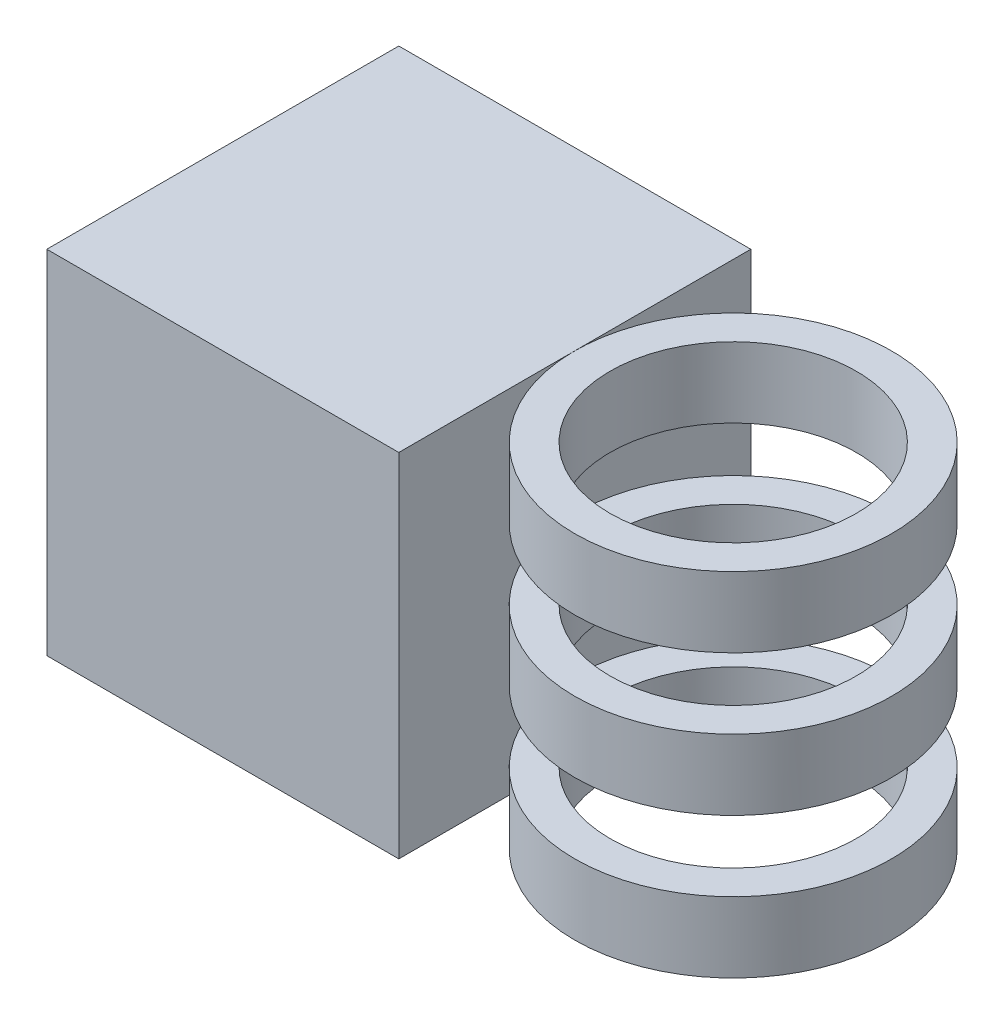
SolidWorks part; units mm, degrees
ref_plane "Front Plane" through (0, 0, 0) normal (0, 0, 1) x (1, 0, 0)
ref_plane "Top Plane" through (0, 0, 0) normal (0, 1, 0) x (1, 0, 0)
ref_plane "Right Plane" through (0, 0, 0) normal (1, 0, 0) x (0, 0, -1)
sketch "Sketch2" plane through (0, 0, 0) normal (0, 0, 1) x (1, 0, 0)
  line L0 (0, 0) -> (0, 5)
  line L1 (0, 5) -> (5, 5)
  line L2 (5, 5) -> (5, 0)
  line L3 (5, 0) -> (0, 0)
  line L4 (5, 5) -> (5, 0) construction
  dimension "D1" = 5
  dimension "D2" = 5
  dimension "D3" = 5
extrude "Boss-Extrude1" add sketch "Sketch2" along normal blind 5
sketch "Sketch4" plane through (0, 5, 0) normal (0, 1, 0) x (1, 0, 0)
  line L0 (5, 0) -> (5, -5) construction
  line L1 (5, 0) -> (0, 0) construction
  line L2 (5, -5) -> (0, -5) construction
  line L3 (0, -5) -> (0, 0) construction
  line L4 (0, -5) -> (8.1714, -5) construction
  point P8 (8.1714, -5)
  dimension "D1" = 5
sketch "Sketch7" plane through (0, 5, 0) normal (0, 1, 0) x (1, 0, 0)
  line L0 (5, -2.5) -> (9.5, -2.5) construction
  line L1 (5, 0) -> (5, -5) construction
  circle A0 centre (7.25, -2.5) radius 2.25
  circle A1 centre (7.25, -2.5) radius 1.75
  dimension "D2" = 4.5
  dimension "D3" = 0.5
  dimension "D1" = 4.5
extrude "Boss-Extrude4" add sketch "Sketch7" against normal blind 5 separate body
sketch "Sketch14" plane through (0, 0, 5) normal (0, 0, 1) x (1, 0, 0)
  line L0 (5, 0) -> (5, 5) construction
  line L1 (5, 4) -> (9.5, 4)
  line L2 (5, 4) -> (5, 3)
  line L3 (5, 3) -> (9.5, 3)
  line L4 (9.5, 4) -> (9.5, 3)
  line L5 (9.5, 0) -> (9.5, 5) construction
  line L6 (0, 5) -> (8.1714, 5) construction
  line L7 (0, 0) -> (5, 0) construction
  line L8 (5, 2) -> (9.5, 2)
  line L9 (5, 2) -> (5, 1)
  line L10 (5, 1) -> (9.5, 1)
  line L11 (9.5, 2) -> (9.5, 1)
  dimension "D1" = 1
  dimension "D2" = 1
  dimension "D3" = 1
  dimension "D4" = 1
extrude "Cut-Extrude8" cut sketch "Sketch14" against normal blind 5
sketch "Sketch15" plane through (0, 5, 0) normal (0, 1, 0) x (1, 0, 0)
